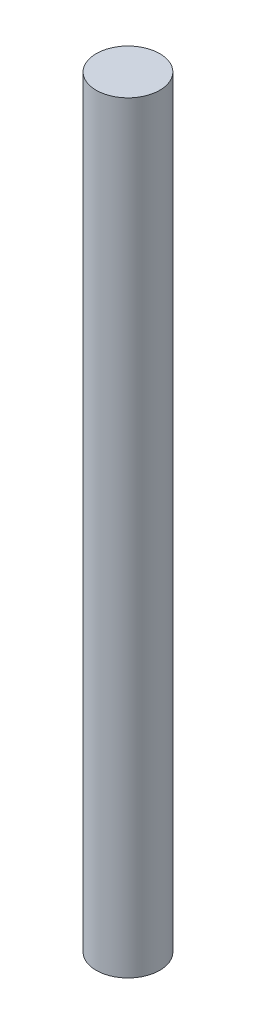
SolidWorks part; units mm, degrees
ref_plane "Front Plane" through (0, 0, 0) normal (0, 0, 1) x (1, 0, 0)
ref_plane "Top Plane" through (0, 0, 0) normal (0, 1, 0) x (1, 0, 0)
ref_plane "Right Plane" through (0, 0, 0) normal (1, 0, 0) x (0, 0, -1)
sketch "Sketch1" plane through (0, 0, 0) normal (0, 1, 0) x (1, 0, 0)
  circle A0 centre (0, 0) radius 4
extrude "Boss-Extrude1" add sketch "Sketch1" along normal blind 96
